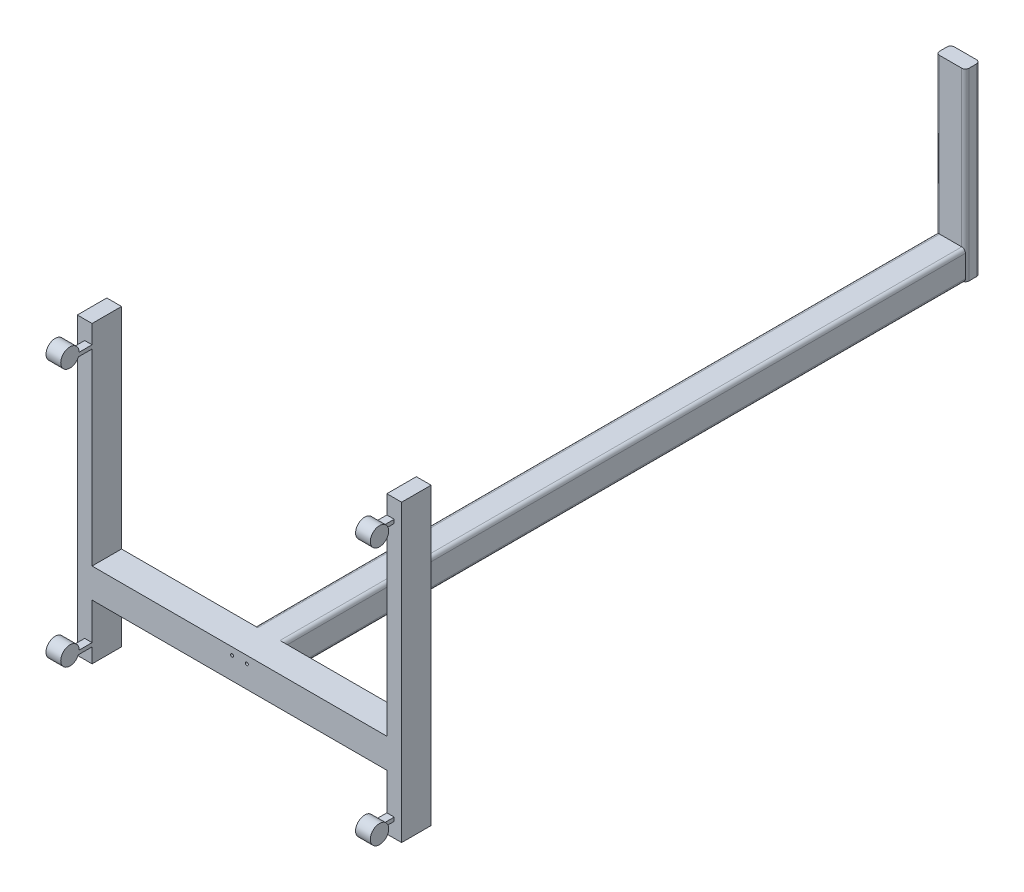
SolidWorks part; units mm, degrees
ref_plane "前视基准面" through (0, 0, 0) normal (0, 0, 1) x (1, 0, 0)
ref_plane "上视基准面" through (0, 0, 0) normal (0, 1, 0) x (1, 0, 0)
ref_plane "右视基准面" through (0, 0, 0) normal (1, 0, 0) x (0, 0, -1)
sketch "草图1" plane through (0, 0, 0) normal (0, 0, 1) x (1, 0, 0)
  line L1 (-400, -40) -> (400, -40)
  line L2 (-400, -40) -> (-400, 40)
  line L3 (-400, 40) -> (400, 40)
  line L4 (400, -40) -> (400, 40)
  line L5 (-400, -40) -> (400, 40) construction
  line L6 (-400, 40) -> (400, -40) construction
  point P0 (0, 0)
  dimension "D1" = 80
  dimension "D2" = 800
extrude "凸台-拉伸1" add sketch "草图1" along normal blind 80
sketch "草图2" plane through (0, 0, 0) normal (0, 0, -1) x (-1, 0, 0)
  line L0 (-400, 40) -> (400, 40) construction
  line L1 (40, -40) -> (-40, -40)
  line L2 (40, -40) -> (40, 40)
  line L3 (40, 40) -> (-40, 40)
  line L4 (-40, -40) -> (-40, 40)
  line L5 (40, -40) -> (-40, 40) construction
  line L6 (40, 40) -> (-40, -40) construction
  point P0 (0, 0)
  dimension "D1" = 80
extrude "凸台-拉伸2" add sketch "草图2" along normal blind 1850 separate body
sketch "草图3" plane through (0, 0, -1850) normal (0, 0, -1) x (-1, 0, 0)
  line L1 (-40, -40) -> (40, -40)
  line L2 (-40, -40) -> (-40, 460)
  line L3 (-40, 460) -> (40, 460)
  line L4 (40, -40) -> (40, 460)
  dimension "D1" = 80
  dimension "D2" = 500
extrude "凸台-拉伸3" add sketch "草图3" along normal blind 40 separate body
sketch "草图4" plane through (-400, 0, 0) normal (-1, 0, 0) x (0, 0, 1)
  line L0 (0, -40) -> (0, 40) construction
  line L1 (0, -190) -> (80, -190)
  line L2 (0, -190) -> (0, 610)
  line L3 (0, 610) -> (80, 610)
  line L4 (80, -190) -> (80, 610)
  line L5 (80, 40) -> (80, -40) construction
  line L6 (-1850, -40) -> (0, -40) construction
  dimension "D1" = 800
  dimension "D2" = 150
extrude "凸台-拉伸4" add sketch "草图4" along normal blind 40 separate body
mirror "镜向2" about plane through (0, 0, 0) normal (1, 0, 0) of bodies 109
sketch "草图5" plane through (440, 0, 0) normal (1, 0, 0) x (0, 0, -1)
  line L0 (1850, 40) -> (0, 40) construction
  line L1 (0, 40) -> (0, -40) construction
  line L2 (0, -190) -> (-80, -190) construction
  circle A0 centre (-20, 20) radius 4
  circle A1 centre (-20, -20) radius 4
  dimension "D1" = 40
  dimension "D2" = 20
  dimension "D3" = 20
  dimension "D4" = 8
  dimension "D5" = 8
  dimension "D6" = 170
  dimension "D7" = 210
extrude "切除-拉伸1" cut sketch "草图5" against normal blind 40
sketch "草图7" plane through (0, 0, 80) normal (0, 0, 1) x (1, 0, 0)
  line L0 (400, 40) -> (-400, 40) construction
  line L1 (400, -40) -> (400, 40) construction
  line L2 (400, -190) -> (400, 610) construction
  circle A0 centre (-20, 20) radius 4
  circle A1 centre (20, 20) radius 4
  dimension "D1" = 8
  dimension "D2" = 8
  dimension "D3" = 20
  dimension "D4" = 20
  dimension "D5" = 40
  dimension "D6" = 380
  dimension "D7" = 420
extrude "切除-拉伸2" cut sketch "草图7" against normal blind 40
sketch "草图8" plane through (0, 0, -1890) normal (0, 0, -1) x (-1, 0, 0)
  line L0 (-40, -40) -> (40, -40) construction
  line L1 (-40, 460) -> (-40, -40) construction
  circle A0 centre (-20, 20) radius 4
  circle A1 centre (-20, -20) radius 4
  dimension "D1" = 8
  dimension "D2" = 8
  dimension "D3" = 40
  dimension "D4" = 20
  dimension "D5" = 20
extrude "切除-拉伸3" [suppressed] cut sketch "草图8" against normal blind 40
fillet "圆角1" radius 10 4 edges at (40, -40, -925) (40, 40, -925) (-40, -40, -925) (-40, 40, -925)
fillet "圆角2" radius 10 4 edges at (40, 210, -1850) (-40, 210, -1850) (40, 210, -1890) (-40, 210, -1890)
sketch "草图9" plane through (-440, 0, 0) normal (-1, 0, 0) x (0, 0, 1)
  line L0 (80, -190) -> (80, 610) construction
  line L1 (0, -190) -> (80, -190) construction
  line L2 (80, 610) -> (0, 610) construction
  circle A0 centre (140, 560) radius 25
  circle A1 centre (140, -140) radius 25
  dimension "D1" = 50
  dimension "D2" = 50
  dimension "D3" = 60
  dimension "D4" = 50
  dimension "D5" = 50
extrude "凸台-拉伸5" add sketch "草图9" against normal blind 40 separate body
sketch "草图10" plane through (-400, 0, 0) normal (1, 0, 0) x (0, 0, -1)
  line L0 (-140, 560) -> (-80, 560)
  line L1 (-80, -190) -> (-80, 610) construction
  line L2 (-140, -140) -> (-80, -140)
extrude "拉伸-薄壁1" add sketch "草图10" against normal blind 20 thin
mirror "镜向6" about plane through (0, 0, 0) normal (1, 0, 0) of bodies 116
combine bodies "组合1" operation type add bodies to combine 112 111 117 107 116
combine bodies "组合2" operation type add bodies to combine 118 108
